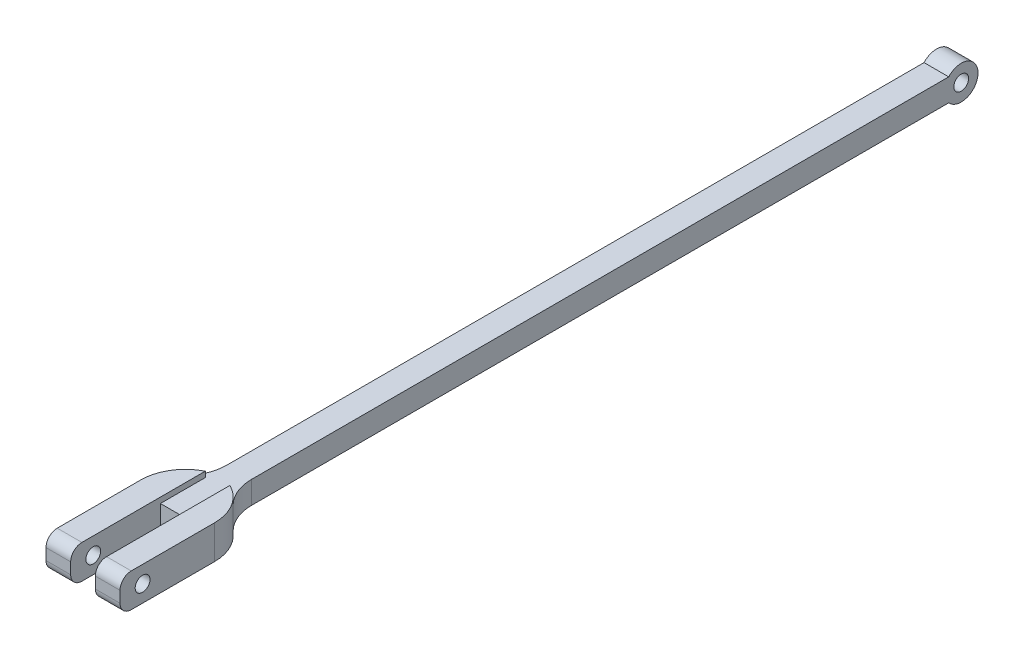
SolidWorks part; units mm, degrees
material "6061 Alloy"
ref_plane "Front Plane" through (0, 0, 0) normal (0, 0, 1) x (1, 0, 0)
ref_plane "Top Plane" through (0, 0, 0) normal (0, 1, 0) x (1, 0, 0)
ref_plane "Right Plane" through (0, 0, 0) normal (1, 0, 0) x (0, 0, -1)
sketch "Sketch1" plane through (0, 0, 0) normal (0, 0, 1) x (1, 0, 0)
  line L1 (6.985, -6.3794) -> (-6.985, -6.3794)
  line L2 (6.985, -6.3794) -> (6.985, 6.3794)
  line L3 (6.985, 6.3794) -> (-6.985, 6.3794)
  line L4 (-6.985, -6.3794) -> (-6.985, 6.3794)
  line L5 (6.985, -6.3794) -> (-6.985, 6.3794) construction
  line L6 (6.985, 6.3794) -> (-6.985, -6.3794) construction
  point P0 (0, 0)
  dimension "D1" = 13.97
extrude "Boss-Extrude1" add sketch "Sketch1" along normal blind 241.3 and the other way blind 198.12
sketch "Sketch2" plane through (0, 0, 0) normal (1, 0, 0) x (0, 0, -1)
  line L0 (198.12, -6.3794) -> (198.12, 6.3794) construction
  circle A0 centre (198.12, 0) radius 9.525
  dimension "D1" = 19.05
extrude "Boss-Extrude2" add sketch "Sketch2" along normal up to surface and the other way up to surface up to face at (6.985, 0, 21.59) other way up to face at (-6.985, 0, 21.59)
sketch "Sketch3" plane through (6.985, 0, 0) normal (1, 0, 0) x (0, 0, -1)
  circle A0 centre (198.12, 0) radius 4.191
  dimension "D1" = 8.382
extrude "Cut-Extrude1" cut sketch "Sketch3" against normal through all
sketch "Sketch4" plane through (0, 0, 0) normal (0, 1, 0) x (1, 0, 0)
  line L0 (-6.985, -241.3) -> (-6.985, -292.1)
  line L1 (-6.985, -292.1) -> (-20.955, -292.1)
  line L2 (-20.955, -292.1) -> (-20.955, -238.5187)
  line L3 (-6.985, 191.0469) -> (-6.985, -241.3) construction
  line L4 (-6.985, -215.9) -> (-6.985, -241.3)
  arc A0 (-20.955, -238.5187) -> (-6.985, -215.9) centre (4.3409, -238.5187) cw
  dimension "D1" = 50.8
  dimension "D2" = 13.97
  dimension "D3" = 25.4
extrude "Boss-Extrude3" add sketch "Sketch4" along normal blind 9.525 and the other way blind 9.525
mirror "Mirror1" about plane through (0, 0, 0) normal (1, 0, 0) of "Boss-Extrude3"
fillet "Fillet4" radius 25.4 2 edges at (6.985, 0, 215.9) (-6.985, 0, 215.9)
fillet "Fillet5" radius 6.35 4 edges at (-13.97, -9.525, 292.1) (13.97, -9.525, 292.1) (13.97, 9.525, 292.1) (-13.97, 9.525, 292.1)
sketch "Sketch6" plane through (0, 0, 0) normal (1, 0, 0) x (0, 0, -1)
  line L2 (23.0505, 0) -> (-23.0505, 0) construction
  circle A0 centre (-279.3245, 0) radius 4.191
  dimension "D1" = 8.382
extrude "Cut-Extrude2" cut sketch "Sketch6" against normal through all and the other way through all
